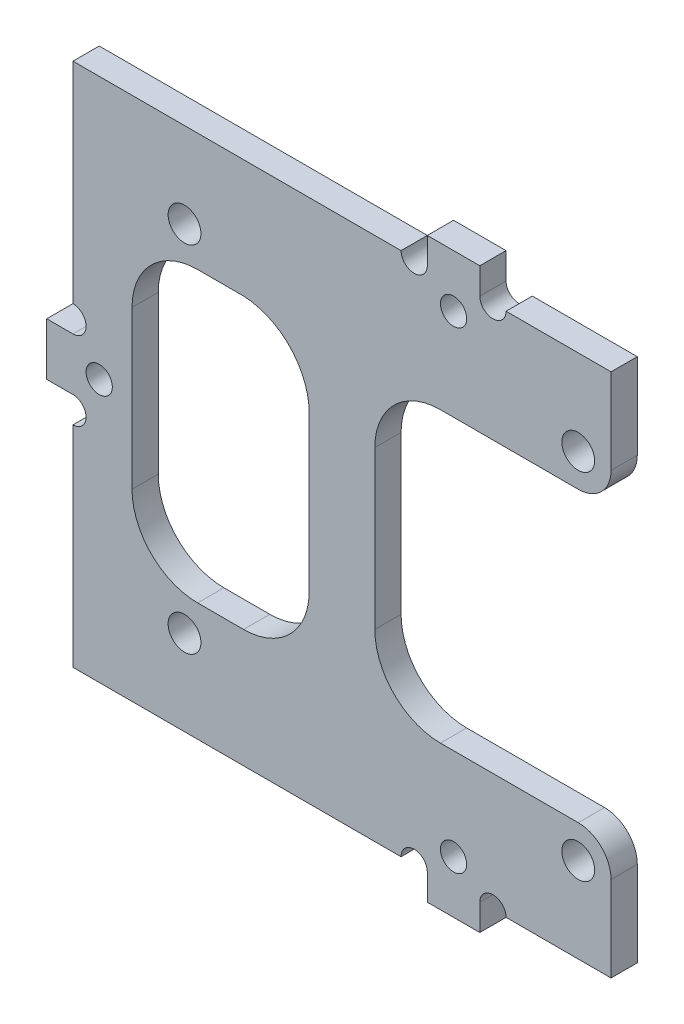
SolidWorks part; units mm, degrees
material "自訂玻璃纖維"
ref_plane "前基準面" through (0, 0, 0) normal (0, 0, 1) x (1, 0, 0)
ref_plane "上基準面" through (0, 0, 0) normal (0, 1, 0) x (1, 0, 0)
ref_plane "右基準面" through (0, 0, 0) normal (1, 0, 0) x (0, 0, -1)
sketch "草圖1" plane through (0, 0, 0) normal (0, 0, 1) x (1, 0, 0)
  line L0 (15.2838, 18.1625) -> (-25.7162, 18.1625)
  line L1 (15.2838, 18.1625) -> (15.2838, -21.8375)
  line L2 (15.2838, -21.8375) -> (-25.7162, -21.8375)
  line L3 (-25.7162, -3.8375) -> (-25.7162, -21.8375)
  line L4 (-25.7162, 0.1625) -> (-27.7162, 0.1625)
  line L6 (-25.7162, -3.8375) -> (-27.7162, -3.8375)
  line L7 (-27.7162, 0.1625) -> (-27.7162, -3.8375)
  line L12 (-25.7162, 18.1625) -> (-25.7162, 0.1625)
  circle A0 centre (-17.2162, 11.6625) radius 1.25
  circle A1 centre (-17.2162, -15.3375) radius 1.25
  circle A2 centre (12.7838, -15.3375) radius 1.25
  circle A3 centre (12.7838, 11.6625) radius 1.25
  circle A4 centre (-23.7162, -1.8375) radius 1
  dimension "D7" = 30
  dimension "D8" = 6.5
  dimension "D10" = 41
  dimension "D12" = 2
  dimension "D13" = 2
  dimension "D4" = 2.5
  dimension "D5" = 30
  dimension "D6" = 27
  dimension "D11" = 2
  dimension "D2" = 2.5
  dimension "D3" = 6.5
  dimension "D14" = 4
  dimension "D15" = 2
extrude "填料-伸長1" add sketch "草圖1" along normal blind 2
sketch "草圖4" plane through (0, 0, 0) normal (0, 0, -1) x (-1, 0, 0)
  line L0 (-15.2838, 9.1625) -> (2.7162, 9.1625)
  line L1 (-15.2838, -21.8375) -> (-15.2838, 18.1625) construction
  line L2 (2.7162, 9.1625) -> (2.7162, -12.8375)
  line L3 (2.7162, -12.8375) -> (-15.2838, -12.8375)
  line L4 (-15.2838, -12.8375) -> (-15.2838, 9.1625)
  circle A0 centre (-12.7838, 11.6625) radius 1.25 construction
  circle A1 centre (-12.7838, -15.3375) radius 1.25 construction
  dimension "D1" = 2.5
  dimension "D2" = 2.5
  dimension "D3" = 18
extrude "除料-伸長1" cut sketch "草圖4" against normal blind 2
fillet "圓角2" radius 2.5 2 edges at (15.2838, -12.8375, 1) (15.2838, 9.1625, 1)
fillet "圓角3" radius 5 2 edges at (-2.7162, -12.8375, 1) (-2.7162, 9.1625, 1)
sketch "草圖5" plane through (0, 0, 0) normal (0, 0, -1) x (-1, 0, 0)
  line L0 (7.7162, 3.948) -> (7.7162, -7.8375)
  line L1 (2.7162, -7.8375) -> (2.7162, 4.1625) construction
  line L2 (12.7162, 9.1625) -> (16.2162, 9.1625)
  line L3 (21.2162, 4.1625) -> (21.2162, -7.8375)
  line L4 (16.2162, -12.8375) -> (12.7162, -12.8375)
  circle A0 centre (17.2162, 11.6625) radius 1.25 construction
  circle A1 centre (17.2162, -15.3375) radius 1.25 construction
  circle A2 centre (23.7162, -1.8375) radius 1 construction
  arc A3 (7.7162, 3.948) -> (12.7162, 9.1625) centre (12.9352, 3.9481) cw
  arc A4 (7.7162, -7.8375) -> (12.7162, -12.8375) centre (12.7162, -7.8375) ccw
  arc A5 (16.2162, 9.1625) -> (21.2162, 4.1625) centre (16.2162, 4.1625) cw
  arc A6 (21.2162, -7.8375) -> (16.2162, -12.8375) centre (16.2162, -7.8375) cw
  dimension "D7" = 5
  dimension "D8" = 5
  dimension "D1" = 5
  dimension "D2" = 2.5
  dimension "D3" = 2.5
  dimension "D4" = 2.5
  dimension "D5" = 5
  dimension "D6" = 5
extrude "除料-伸長2" cut sketch "草圖5" against normal blind 2
sketch "草圖7" plane through (0, 0, 0) normal (0, 0, -1) x (-1, 0, 0)
  circle A1 centre (-3.2838, -19.8375) radius 1
  circle A3 centre (-3.2838, 16.1625) radius 1
  dimension "D1" = 2
extrude "除料-伸長3" cut sketch "草圖7" against normal blind 10
sketch "草圖8" plane through (0, 0, 0) normal (0, 0, -1) x (-1, 0, 0)
  line L0 (25.7162, -21.8375) -> (-15.2838, -21.8375) construction
  line L1 (-15.2838, 18.1625) -> (25.7162, 18.1625) construction
  line L2 (-5.2838, -21.8375) -> (-5.2838, -23.8375)
  line L3 (-5.2838, -23.8375) -> (-1.2838, -23.8375)
  line L4 (-1.2838, -21.8375) -> (-1.2838, -23.8375)
  line L5 (-5.2838, 18.1625) -> (-1.2838, 18.1625)
  line L6 (-5.2838, 18.1625) -> (-5.2838, 20.1625)
  line L7 (-5.2838, 20.1625) -> (-1.2838, 20.1625)
  line L8 (-1.2838, 18.1625) -> (-1.2838, 20.1625)
  line L9 (25.7162, 18.1625) -> (25.7162, 0.1625) construction
  line L10 (25.7162, 0.1625) -> (27.7162, 0.1625)
  line L11 (25.7162, 0.1625) -> (25.7162, -3.8375)
  line L12 (25.7162, -3.8375) -> (27.7162, -3.8375)
  line L13 (27.7162, 0.1625) -> (27.7162, -3.8375)
  circle A0 centre (-3.2838, -19.8375) radius 1 construction
  circle A1 centre (-3.2838, 16.1625) radius 1 construction
  circle A2 centre (23.7162, -1.8375) radius 1 construction
  line M17 (25.7162, 18.1625) -> (-15.2838, 18.1625)
  line M29 (-15.2838, -21.8375) -> (25.7162, -21.8375)
  dimension "D4" = 4
  dimension "D1" = 4
  dimension "D2" = 2
  dimension "D3" = 2
  dimension "D5" = 2
  dimension "D6" = 2
  dimension "D7" = 2
  dimension "D8" = 4
  dimension "D9" = 2
extrude "填料-伸長2" add sketch "草圖8" against normal blind 2 contours L8 L7 L6 M17 | L4 L2 L3 M29
sketch "草圖9" plane through (0, 0, 0) normal (0, 0, -1) x (-1, 0, 0)
  line L0 (-15.2838, 18.1625) -> (-5.2838, 18.1625) construction
  line L1 (-1.2838, 18.1625) -> (25.7162, 18.1625) construction
  line L2 (-5.2838, -21.8375) -> (-15.2838, -21.8375) construction
  line L3 (25.7162, -21.8375) -> (-1.2838, -21.8375) construction
  line L4 (-7.2838, 18.1625) -> (-5.2838, 18.1625)
  line L5 (-1.2838, 18.1625) -> (0.7162, 18.1625)
  line L6 (-7.2838, -21.8375) -> (-5.2838, -21.8375)
  line L7 (-1.2838, -21.8375) -> (0.7162, -21.8375)
  line L8 (25.7162, 18.1625) -> (25.7162, 0.1625) construction
  line L9 (25.7162, -3.8375) -> (25.7162, -21.8375) construction
  line L10 (25.7162, 2.1625) -> (25.7162, 0.1625)
  line L12 (25.7162, -3.8375) -> (25.7162, -5.8375)
  arc A0 (-5.2838, 18.1625) -> (-7.2838, 18.1625) centre (-6.2838, 18.1625) cw
  arc A1 (-1.2838, 18.1625) -> (0.7162, 18.1625) centre (-0.2838, 18.1625) ccw
  arc A2 (-5.2838, -21.8375) -> (-7.2838, -21.8375) centre (-6.2838, -21.8375) ccw
  arc A3 (-1.2838, -21.8375) -> (0.7162, -21.8375) centre (-0.2838, -21.8375) cw
  arc A4 (25.7162, 0.1625) -> (25.7162, 2.1625) centre (25.7162, 1.1625) cw
  arc A5 (25.7162, -3.8375) -> (25.7162, -5.8375) centre (25.7162, -4.8375) ccw
  dimension "D1" = 1
extrude "除料-伸長4" cut sketch "草圖9" against normal blind 2
